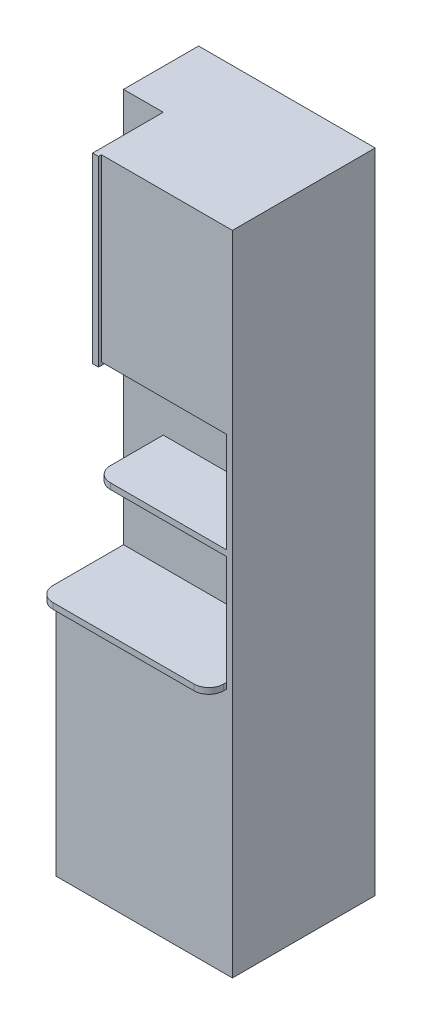
SolidWorks part; units mm, degrees
ref_plane "정면" through (0, 0, 0) normal (0, 0, 1) x (1, 0, 0)
ref_plane "윗면" through (0, 0, 0) normal (0, 1, 0) x (1, 0, 0)
ref_plane "우측면" through (0, 0, 0) normal (1, 0, 0) x (0, 0, -1)
sketch "스케치1" plane through (0, 0, 0) normal (0, 0, 1) x (1, 0, 0)
  line L1 (0.3, 1.1) -> (-0.3, 1.1)
  line L2 (0.3, 1.1) -> (0.3, -1.1)
  line L3 (0.3, -1.1) -> (-0.3, -1.1)
  line L4 (-0.3, 1.1) -> (-0.3, -1.1)
  line L5 (0.3, 1.1) -> (-0.3, -1.1) construction
  line L6 (0.3, -1.1) -> (-0.3, 1.1) construction
  point P0 (0, 0)
  dimension "D1" = 0.6
  dimension "D2" = 2.2
extrude "보스-돌출1" add sketch "스케치1" along normal blind 0.485
sketch "스케치2" plane through (-0.3, 0, 0) normal (-1, 0, 0) x (0, 0, 1)
  line L0 (0.485, -1.1) -> (0, -1.1) construction
  line L1 (0.485, 1.1) -> (0.255, 1.1)
  line L2 (0.485, 1.1) -> (0.485, -0.26)
  line L3 (0.485, -0.26) -> (0.255, -0.26)
  line L4 (0.255, 1.1) -> (0.255, -0.26)
  dimension "D1" = 0.23
  dimension "D2" = 0.84
extrude "컷-돌출1" cut sketch "스케치2" against normal blind 0.135
sketch "스케치3" plane through (-0.165, 0, 0) normal (-1, 0, 0) x (0, 0, 1)
  line L0 (0.485, -0.26) -> (0.485, 1.1) construction
  line L1 (0.485, 0.13) -> (0.255, 0.13)
  line L2 (0.485, 0.13) -> (0.485, -0.26)
  line L3 (0.485, -0.26) -> (0.255, -0.26)
  line L4 (0.255, 0.13) -> (0.255, -0.26)
  line L5 (0.255, 1.1) -> (0.255, -0.26) construction
  line L6 (0.255, -0.26) -> (0.485, -0.26) construction
  dimension "D1" = 0.39
  dimension "D2" = 0
extrude "컷-돌출2" cut sketch "스케치3" against normal blind 0.445
sketch "스케치4" plane through (-0.165, 0, 0) normal (-1, 0, 0) x (0, 0, 1)
  line L0 (0.485, 0.13) -> (0.485, 1.1) construction
  line L1 (0.485, 0.49) -> (0.255, 0.49)
  line L2 (0.485, 0.49) -> (0.485, 0.15)
  line L3 (0.485, 0.15) -> (0.255, 0.15)
  line L4 (0.255, 0.49) -> (0.255, 0.15)
  line L5 (0.255, 1.1) -> (0.255, 0.13) construction
  line L6 (0.485, 0.13) -> (0.255, 0.13) construction
  dimension "D1" = 0.34
  dimension "D2" = 0.02
extrude "컷-돌출3" cut sketch "스케치4" against normal blind 0.445
sketch "스케치6" plane through (-0.165, 0, 0) normal (-1, 0, 0) x (0, 0, 1)
  line L1 (0.485, 1.1) -> (0.255, 1.1)
  line L2 (0.485, 1.1) -> (0.485, 0.49)
  line L3 (0.485, 0.49) -> (0.255, 0.49)
  line L4 (0.255, 1.1) -> (0.255, 0.49)
extrude "컷-돌출4" cut sketch "스케치6" against normal blind 0.02
sketch "스케치7" plane through (-0.145, 0, 0) normal (-1, 0, 0) x (0, 0, 1)
  line L1 (0.255, 1.1) -> (0.495, 1.1)
  line L2 (0.255, 1.1) -> (0.255, 0.48)
  line L3 (0.255, 0.48) -> (0.495, 0.48)
  line L4 (0.495, 1.1) -> (0.495, 0.48)
  dimension "D1" = 0.62
  dimension "D2" = 0.24
extrude "보스-돌출2" add sketch "스케치7" along normal blind 0.02
sketch "스케치8" plane through (0, -0.26, 0) normal (0, 1, 0) x (1, 0, 0)
  line L1 (0.28, -0.255) -> (-0.3, -0.255)
  line L2 (0.28, -0.255) -> (0.28, -0.545)
  line L3 (0.28, -0.545) -> (-0.3, -0.545)
  line L4 (-0.3, -0.255) -> (-0.3, -0.545)
  dimension "D1" = 0.29
  dimension "D2" = 0.58
extrude "보스-돌출3" add sketch "스케치8" along normal blind 0.02
fillet "필렛1" radius 0.05 1 edges at (-0.3, -0.25, 0.545)
fillet "필렛2" radius 0.05 1 edges at (-0.165, 0.14, 0.485)
fillet "필렛3" radius 0.05 1 edges at (0.28, -0.25, 0.545)
